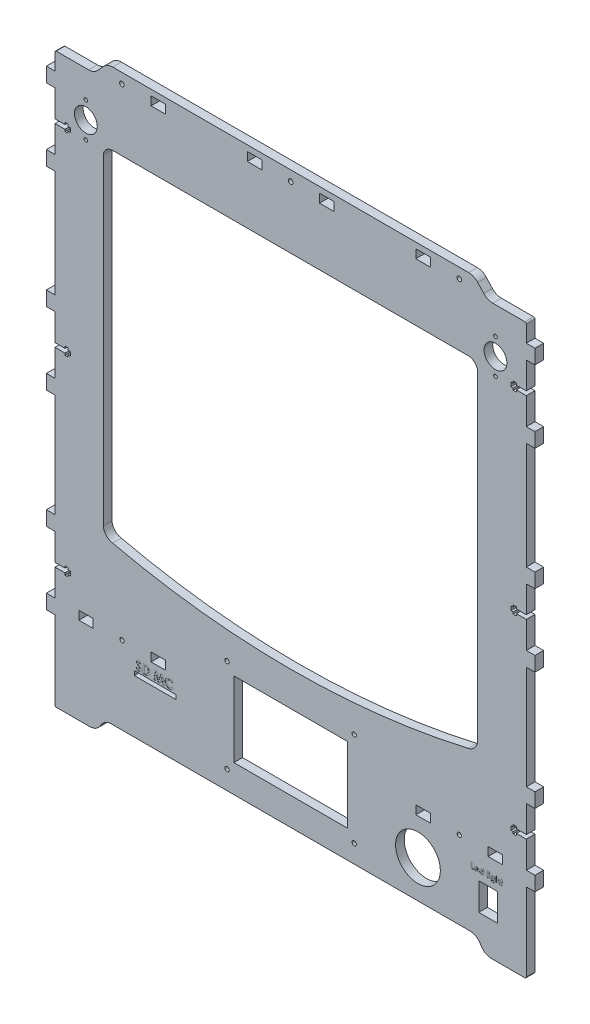
SolidWorks part; units mm, degrees
ref_plane "Спереди" through (0, 0, 0) normal (0, 0, 1) x (1, 0, 0)
ref_plane "Сверху" through (0, 0, 0) normal (0, 1, 0) x (1, 0, 0)
ref_plane "Справа" through (0, 0, 0) normal (1, 0, 0) x (0, 0, -1)
sketch "Эскиз1" plane through (0, 0, 0) normal (0, 0, 1) x (1, 0, 0)
  line L0 (-95.8892, 197.3491) -> (-85.8892, 197.3491)
  line L1 (-85.8892, 197.3491) -> (-85.8892, 191.3491)
  line L2 (-85.8892, 191.3491) -> (-95.8892, 191.3491)
  line L3 (-95.8892, 191.3491) -> (-95.8892, 197.3491)
  line L4 (97.3908, 191.3491) -> (87.3908, 191.3491)
  line L5 (87.3908, 191.3491) -> (87.3908, 197.3491)
  line L6 (87.3908, 197.3491) -> (97.3908, 197.3491)
  line L7 (97.3908, 197.3491) -> (97.3908, 191.3491)
  line L8 (97.3654, -141.9477) -> (87.3654, -141.9477)
  line L9 (87.3654, -141.9477) -> (87.3654, -135.9477)
  line L10 (87.3654, -135.9477) -> (97.3654, -135.9477)
  line L11 (97.3654, -135.9477) -> (97.3654, -141.9477)
  line L12 (147.3854, -141.9477) -> (137.3854, -141.9477)
  line L13 (137.3854, -141.9477) -> (137.3854, -135.9477)
  line L14 (137.3854, -135.9477) -> (147.3854, -135.9477)
  line L15 (147.3854, -135.9477) -> (147.3854, -141.9477)
  line L16 (-135.8946, -141.9477) -> (-145.8946, -141.9477)
  line L17 (-145.8946, -141.9477) -> (-145.8946, -135.9477)
  line L18 (-145.8946, -135.9477) -> (-135.8946, -135.9477)
  line L19 (-135.8946, -135.9477) -> (-135.8946, -141.9477)
  line L20 (-85.8746, -141.9477) -> (-95.8746, -141.9477)
  line L21 (-95.8746, -141.9477) -> (-95.8746, -135.9477)
  line L22 (-95.8746, -135.9477) -> (-85.8746, -135.9477)
  line L23 (-85.8746, -135.9477) -> (-85.8746, -141.9477)
  line L24 (-19.2392, 191.3491) -> (-29.2392, 191.3491)
  line L25 (-29.2392, 191.3491) -> (-29.2392, 197.3491)
  line L26 (-29.2392, 197.3491) -> (-19.2392, 197.3491)
  line L27 (-19.2392, 197.3491) -> (-19.2392, 191.3491)
  line L28 (30.7408, 191.3491) -> (20.7408, 191.3491)
  line L29 (20.7408, 191.3491) -> (20.7408, 197.3491)
  line L30 (20.7408, 197.3491) -> (30.7408, 197.3491)
  line L31 (30.7408, 197.3491) -> (30.7408, 191.3491)
  line L32 (-122.3991, 151.3491) -> (123.6241, 151.3491)
  line L33 (40.0454, -173.6357) -> (40.0454, -121.6361)
  line L34 (40.0454, -121.6361) -> (-38.5546, -121.6361)
  line L35 (-38.5546, -121.6361) -> (-38.5546, -173.6357)
  line L36 (-38.5546, -173.6357) -> (40.0454, -173.6357)
  line L37 (143.9388, -159.6762) -> (143.9388, -178.6762)
  line L38 (143.9388, -178.6762) -> (130.9388, -178.6762)
  line L39 (130.9388, -178.6762) -> (130.9388, -159.6762)
  line L40 (130.9388, -159.6762) -> (143.9388, -159.6762)
  line L41 (-162.3492, -146.9309) -> (-168.3546, -146.9309)
  line L42 (-168.3546, -146.9309) -> (-168.3546, -136.9309)
  line L43 (-168.3546, -136.9309) -> (-162.3546, -136.9309)
  line L44 (-162.3546, -136.9309) -> (-162.3546, -118.3209)
  line L45 (-162.3546, -96.9409) -> (-168.3546, -96.9409)
  line L46 (-168.3546, -96.9409) -> (-168.3546, -86.9409)
  line L47 (-168.3546, -86.9409) -> (-162.3546, -86.9409)
  line L48 (-162.3546, -86.9409) -> (-162.3546, -15.2109)
  line L49 (-162.3546, -15.2109) -> (-168.3546, -15.2109)
  line L50 (-162.3546, 34.7891) -> (-168.3546, 34.7891)
  line L51 (-168.3546, -5.2109) -> (-162.3546, -5.2109)
  line L52 (-168.3546, 44.7891) -> (-162.3546, 44.7891)
  line L56 (-162.3546, 128.9491) -> (-162.3546, 147.5491)
  line L57 (-162.3492, 168.9491) -> (-168.3492, 168.9491)
  line L58 (-168.3492, 168.9491) -> (-168.3492, 178.9491)
  line L59 (-168.3492, 178.9491) -> (-162.3492, 178.9491)
  line L60 (-162.3492, 178.9491) -> (-162.3492, 190.3491)
  line L61 (-162.3492, -200.9709) -> (-162.3492, -146.9309)
  line L62 (163.8454, -146.9309) -> (169.8454, -146.9309)
  line L63 (169.8454, -146.9309) -> (169.8454, -136.9309)
  line L64 (169.8454, -136.9309) -> (163.8513, -136.9309)
  line L65 (163.8513, -136.9309) -> (163.8513, -118.3209)
  line L66 (163.9392, -96.9409) -> (169.8512, -96.9409)
  line L67 (169.8512, -96.9409) -> (169.8512, -86.9409)
  line L68 (169.8512, -86.9409) -> (163.8512, -86.9409)
  line L69 (163.8512, -86.9409) -> (163.8512, -15.2109)
  line L70 (163.8512, -15.2109) -> (169.8512, -15.2109)
  line L71 (163.8512, 34.7891) -> (169.8512, 34.7891)
  line L72 (169.8512, -5.2109) -> (163.8512, -5.2109)
  line L73 (169.8512, 44.7891) -> (163.8512, 44.7891)
  line L74 (163.8512, 118.9491) -> (169.8512, 118.9491)
  line L75 (169.8512, 118.9491) -> (169.8512, 128.9491)
  line L76 (169.8512, 128.9491) -> (163.8512, 128.9491)
  line L77 (163.8512, 128.9491) -> (163.8512, 147.5491)
  line L78 (163.8508, 168.9491) -> (169.8508, 168.9491)
  line L79 (169.8508, 168.9491) -> (169.8508, 178.9491)
  line L80 (169.8508, 178.9491) -> (163.8508, 178.9491)
  line L81 (163.8508, 178.9491) -> (163.8508, 190.3491)
  line L82 (156.9388, 150.3491) -> (156.9388, 151.7492)
  line L83 (163.9392, -115.5209) -> (156.9392, -115.5209)
  line L84 (156.9392, -114.1224) -> (154.7382, -114.1224)
  line L85 (156.9399, -118.3209) -> (163.8513, -118.3209)
  line L86 (153.2384, -118.3222) -> (154.7405, -118.3222)
  line L87 (-155.4441, 11.989) -> (-153.2432, 11.989)
  line L88 (154.7382, -114.1224) -> (154.7382, -115.5222)
  line L89 (154.7391, 16.1893) -> (153.24, 16.1893)
  line L90 (153.2384, -115.5222) -> (153.2384, -118.3222)
  line L91 (-155.4426, -119.721) -> (-153.2418, -119.721)
  line L92 (163.8508, 150.3491) -> (156.9388, 150.3491)
  line L93 (156.9399, -119.7231) -> (156.9399, -118.3209)
  line L94 (156.9392, -115.5209) -> (156.9392, -114.1224)
  line L95 (154.7382, -115.5222) -> (153.2384, -115.5222)
  line L96 (154.741, 147.5502) -> (154.741, 146.1493)
  line L97 (-155.4451, -114.1209) -> (-155.4451, -115.5209)
  line L98 (154.7415, 13.3902) -> (154.7415, 11.9893)
  line L99 (-162.3546, 147.5491) -> (-155.4441, 147.5491)
  line L100 (-155.4441, 147.5491) -> (-155.4441, 146.149)
  line L101 (-155.4398, 150.3491) -> (-162.3492, 150.3491)
  line L102 (-153.2398, 150.3482) -> (-153.2398, 151.7491)
  line L103 (154.7405, -118.3222) -> (154.7405, -119.7231)
  line L104 (-155.4451, -115.5209) -> (-162.3546, -115.5209)
  line L105 (154.741, 151.7492) -> (154.741, 150.3493)
  line L106 (156.9417, 146.1493) -> (156.9417, 147.5491)
  line L107 (-153.2432, 13.3622) -> (-151.7428, 13.3622)
  line L108 (-155.4426, -118.3209) -> (-155.4426, -119.721)
  line L109 (153.241, 150.3493) -> (153.241, 147.5502)
  line L110 (-153.2451, 17.5891) -> (-155.4451, 17.5891)
  line L111 (-162.3546, 13.3891) -> (-155.4441, 13.3891)
  line L112 (154.741, 146.1493) -> (156.9417, 146.1493)
  line L113 (153.241, 147.5502) -> (154.741, 147.5502)
  line L114 (-153.2433, 147.5489) -> (-151.7375, 147.5489)
  line L115 (-151.7428, 13.3622) -> (-151.7428, 16.1885)
  line L116 (163.8512, 16.1891) -> (156.9392, 16.1891)
  line L117 (154.7391, 17.5621) -> (154.7391, 16.1893)
  line L118 (154.741, 150.3493) -> (153.241, 150.3493)
  line L119 (154.7415, 11.9893) -> (156.9417, 11.9893)
  line L120 (-153.2451, -114.1209) -> (-155.4451, -114.1209)
  line L121 (-151.7436, -118.3211) -> (-151.7436, -115.5218)
  line L122 (-153.2418, -118.3211) -> (-151.7436, -118.3211)
  line L123 (-153.2432, 11.989) -> (-153.2432, 13.3622)
  line L124 (156.9417, 13.3891) -> (163.8512, 13.3891)
  line L125 (-162.3546, -118.3209) -> (-155.4426, -118.3209)
  line L126 (153.24, 16.1893) -> (153.24, 13.3902)
  line L127 (-153.2451, -115.5218) -> (-153.2451, -114.1209)
  line L128 (-151.7428, 16.1885) -> (-153.2451, 16.1885)
  line L129 (-155.4441, 146.149) -> (-153.2433, 146.149)
  line L130 (-153.2418, -119.721) -> (-153.2418, -118.3211)
  line L131 (-155.4398, 151.7491) -> (-155.4398, 150.3491)
  line L132 (-151.7436, -115.5218) -> (-153.2451, -115.5218)
  line L133 (-153.2433, 146.149) -> (-153.2433, 147.5489)
  line L134 (153.24, 13.3902) -> (154.7415, 13.3902)
  line L135 (156.9388, 151.7492) -> (154.741, 151.7492)
  line L136 (-151.7375, 147.5489) -> (-151.738, 150.3482)
  line L137 (156.9417, 147.5491) -> (163.8512, 147.5491)
  line L138 (-155.4451, 16.1891) -> (-162.3546, 16.1891)
  line L139 (156.9417, 11.9893) -> (156.9417, 13.3891)
  line L140 (-155.4451, 17.5891) -> (-155.4451, 16.1891)
  line L141 (154.7405, -119.7231) -> (156.9399, -119.7231)
  line L142 (-153.2398, 151.7491) -> (-155.4398, 151.7491)
  line L143 (156.9392, 17.5621) -> (154.7391, 17.5621)
  line L144 (-151.738, 150.3482) -> (-153.2398, 150.3482)
  line L145 (-162.3546, -115.5209) -> (-162.3546, -96.9409)
  line L146 (-162.3492, 150.3491) -> (-162.3492, 168.9491)
  line L147 (163.9392, -115.5209) -> (163.9392, -96.9409)
  line L148 (163.8508, 150.3491) -> (163.8508, 168.9491)
  line L149 (-139.0924, 191.3491) -> (-161.5253, 191.3491)
  line L150 (-128.7242, 198.5879) -> (-132.8221, 194.1104)
  line L151 (123.9554, 201.3491) -> (-122.4539, 201.3491)
  line L152 (130.2257, 198.5879) -> (134.3236, 194.1104)
  line L153 (140.5939, 191.3491) -> (162.8508, 191.3491)
  line L154 (-131.8015, -198.9146) -> (-129.7448, -195.8949)
  line L155 (162.7628, -201.9477) -> (139.7264, -201.9477)
  line L156 (133.303, -198.9146) -> (131.2463, -195.8949)
  line L157 (-161.4373, -201.9509) -> (-138.3129, -201.9509)
  line L158 (-123.2334, -192.8586) -> (124.7349, -192.8586)
  line L159 (163.8454, -200.9731) -> (163.8454, -146.9309)
  line L160 (-162.3546, 13.3891) -> (-162.3546, -5.2109)
  line L161 (-168.3546, -15.2109) -> (-168.3546, -5.2109)
  line L162 (-168.3546, 34.7891) -> (-168.3546, 44.7891)
  line L163 (-162.3546, 44.7891) -> (-162.3546, 118.9491)
  line L164 (163.8512, 13.3891) -> (163.8512, -5.2109)
  line L165 (169.8512, -15.2109) -> (169.8512, -5.2109)
  line L166 (169.8512, 34.7891) -> (169.8512, 44.7891)
  line L167 (163.8512, 44.7891) -> (163.8512, 118.9491)
  line L168 (-155.4441, 13.3891) -> (-155.4441, 11.989)
  line L169 (-153.2451, 16.1885) -> (-153.2451, 17.5891)
  line L170 (156.9392, 16.1891) -> (156.9392, 17.5621)
  line L171 (-162.3546, 34.7891) -> (-162.3546, 16.1891)
  line L172 (163.8512, 34.7891) -> (163.8512, 16.1891)
  line L173 (-107.5042, -155.9271) -> (-107.5042, -152.9271)
  line L174 (-107.5042, -152.9271) -> (-78.5042, -152.9271)
  line L175 (-78.5042, -152.9271) -> (-78.5042, -155.9271)
  line L176 (-78.5042, -155.9271) -> (-107.5042, -155.9271)
  line L177 (-162.3546, 128.9491) -> (-168.3546, 128.9491)
  line L178 (-162.3546, 118.9491) -> (-168.3546, 118.9491)
  line L179 (-168.3546, 118.9491) -> (-168.3546, 128.9491)
  line L180 (-155.4426, -141.9477) -> (156.9399, -141.9477) construction
  line L181 (-140.9992, 144.3414) -> (-140.9992, 175.9536) construction
  line L182 (142.5008, 178.9491) -> (142.5008, 143.1493) construction
  line L183 (130.1588, 145.3729) -> (130.1254, -76.9742)
  line L184 (-128.9341, 145.3729) -> (-128.9472, -76.974)
  arc A0 (-122.4711, -84.0153) -> (123.6489, -84.0153) centre (0.5889, 449.8336) ccw
  circle A3 centre (44.7454, -115.1361) radius 1.5
  circle A4 centre (44.7454, -180.3857) radius 1.5
  circle A5 centre (-43.2546, -179.8825) radius 1.5
  circle A6 centre (-43.2546, -115.1361) radius 1.5
  circle A7 centre (88.8454, -166.9477) radius 15.5
  arc A8 (130.1588, 145.3729) -> (123.6241, 151.3491) centre (123.6241, 144.7884) ccw
  arc A9 (-122.3991, 151.3491) -> (-128.9341, 145.3729) centre (-122.472, 144.8677) ccw
  arc A10 (-128.9472, -76.974) -> (-122.4711, -84.0153) centre (-121.245, -76.3888) ccw
  arc A11 (123.6489, -84.0153) -> (130.1254, -76.9742) centre (121.7477, -75.7674) ccw
  circle A12 centre (0.7508, 194.3491) radius 1.6
  circle A13 centre (-116.0492, 194.3491) radius 1.6
  arc A14 (134.3236, 194.1104) -> (140.5939, 191.3491) centre (140.5939, 199.8491) ccw
  arc A15 (-161.5253, 191.3491) -> (-162.3492, 190.3491) centre (-161.4373, 190.4372) ccw
  arc A16 (-139.0924, 191.3491) -> (-132.8221, 194.1104) centre (-139.0924, 199.8491) ccw
  arc A17 (-122.4539, 201.3491) -> (-128.7242, 198.5879) centre (-122.4539, 192.8491) ccw
  circle A18 centre (117.5508, 194.3491) radius 1.6
  arc A19 (130.2257, 198.5879) -> (123.9554, 201.3491) centre (123.9554, 192.8491) ccw
  arc A20 (163.8508, 190.3491) -> (162.8508, 191.3491) centre (162.8508, 190.3491) ccw
  arc A21 (-123.2334, -192.8586) -> (-129.7448, -195.8949) centre (-123.2334, -201.3586) ccw
  arc A22 (-138.3129, -201.9509) -> (-131.8015, -198.9146) centre (-138.3129, -193.4509) ccw
  arc A23 (131.2463, -195.8949) -> (124.7349, -192.8586) centre (124.7349, -201.3586) ccw
  arc A24 (133.303, -198.9146) -> (139.7264, -201.9477) centre (139.7677, -193.542) ccw
  arc A25 (-162.3492, -200.9709) -> (-161.4373, -201.9509) centre (-161.3926, -200.9949) ccw
  arc A26 (162.7628, -201.9477) -> (163.8454, -200.9731) centre (162.8028, -200.9035) ccw
  circle A27 centre (-140.9992, 160.3491) radius 7.9
  circle A28 centre (142.5008, 160.3491) radius 7.9
  circle A29 centre (-115.9946, -138.9477) radius 1.5
  circle A30 centre (117.4854, -138.9477) radius 1.5
  circle A31 centre (-140.9992, 172.3491) radius 1.25
  circle A32 centre (-140.9992, 148.3491) radius 1.25
  circle A33 centre (142.5008, 172.3491) radius 1.25
  circle A34 centre (142.5008, 148.3491) radius 1.25
  point P239 (87.3908, 194.3491)
  point P241 (-162.3492, 184.6491)
  dimension "D11" = 15.8
  dimension "D12" = 15.8
  dimension "D53" = 31
  dimension "D88" = 283.5
  dimension "D115" = 2.5
  dimension "D113" = 2.5
  dimension "D116" = 12
  dimension "D117" = 12
  dimension "D118" = 2.5
  dimension "D119" = 2.5
  dimension "D120" = 12
  dimension "D121" = 12
  dimension "D1" = 10
  dimension "D2" = 12.4
  dimension "D3" = 12.4
  dimension "D4" = 10
  dimension "D5" = 18.6
  dimension "D6" = 2.8
  dimension "D7" = 18.6
  dimension "D8" = 10
  dimension "D9" = 10
  dimension "D10" = 10
  dimension "D13" = 6
  dimension "D14" = 18.6
  dimension "D15" = 18.6
  dimension "D16" = 10
  dimension "D17" = 74.16
  dimension "D18" = 74.16
  dimension "D19" = 10
  dimension "D20" = 10
  dimension "D21" = 18.6
  dimension "D22" = 18.6
  dimension "D23" = 18.6
  dimension "D24" = 18.6
  dimension "D25" = 10
  dimension "D26" = 10
  dimension "D27" = 71.73
  dimension "D28" = 71.73
  dimension "D29" = 10
  dimension "D30" = 10
  dimension "D31" = 18.58
  dimension "D32" = 18.58
  dimension "D33" = 18.61
  dimension "D34" = 18.61
  dimension "D35" = 10
  dimension "D36" = 10
  dimension "D37" = 54.04
  dimension "D38" = 54.0422
  dimension "D39" = 403.2968
  dimension "D40" = 2.8
  dimension "D41" = 2.8
  dimension "D42" = 2.8
  dimension "D43" = 2.8
  dimension "D44" = 403.3
  dimension "D45" = 10
  dimension "D46" = 10
  dimension "D47" = 10
  dimension "D48" = 169.1
  dimension "D49" = 10
  dimension "D50" = 10
  dimension "D51" = 10
  dimension "D52" = 10
  dimension "D54" = 338.2
  dimension "D55" = 169.1
  dimension "D56" = 10
  dimension "D57" = 52.3
  dimension "D58" = 52.3
  dimension "D59" = 72.46
  dimension "D60" = 72.46
  dimension "D61" = 56.65
  dimension "D62" = 56.65
  dimension "D63" = 19.99
  dimension "D64" = 19.99
  dimension "D65" = 21.35
  dimension "D66" = 21.35
  dimension "D67" = 22.46
  dimension "D68" = 22.46
  dimension "D69" = 19.9
  dimension "D70" = 19.9
  dimension "D71" = 20.12
  dimension "D72" = 20.12
  dimension "D73" = 47.32
  dimension "D74" = 78.6
  dimension "D75" = 47.32
  dimension "D76" = 4.7
  dimension "D77" = 4.7
  dimension "D78" = 4.7
  dimension "D79" = 4.7
  dimension "D80" = 6.5
  dimension "D81" = 6.5
  dimension "D82" = 6
  dimension "D83" = 60
  dimension "D84" = 55.02
  dimension "D85" = 6
  dimension "D86" = 29
  dimension "D87" = 3
  dimension "D89" = 4
  dimension "D90" = 7
  dimension "D91" = 6
  dimension "D92" = 4
  dimension "D93" = 6
  dimension "D94" = 7
  dimension "D95" = 4
  dimension "D96" = 6
  dimension "D97" = 4
  dimension "D98" = 2.8
  dimension "D99" = 7
  dimension "D100" = 31
  dimension "D101" = 31
  dimension "D102" = 166.56
  dimension "D103" = 131.73
  dimension "D104" = 51.9996
  dimension "D105" = 6
  dimension "D106" = 3
  dimension "D107" = 6
  dimension "D108" = 3
  dimension "D109" = 6
  dimension "D110" = 25
  dimension "D111" = 6
  dimension "D112" = 75
  dimension "D114" = 326.2
  dimension "D122" = 50
  dimension "D123" = 13
  dimension "D124" = 19
extrude "Бобышка-Вытянуть2" add sketch "Эскиз1" along normal blind 6 contours A5 | A4 | A3 | A13 | A12 | A7 | A6 | L32 A8 L183 A11 A0 A10 L184 A9 | A18 | A30 | A29 | A28 | A27 | L4 L5 L6 L7 | L0 L1 L2 L3 | L20 L21 L22 L23 | L16 L17 L18 L19 | L12 L13 L14 L15 | L8 L9 L10 L11 | L37 L38 L39 L40 | L33 L34 L35 L36 | L28 L29 L30 L31 | L24 L25 L26 L27 | L41 L42 L43 L44 L125 L108 L91 L130 L122 L121 L132 L127 L120 L97 L104 L145 L45 L46 L47 L48 L49 L161 L51 L160 L111 L168 L87 L123 L107 L115 L128 L169 L110 L140 L138 L171 L50 L162 L52 L163 L178 L179 L177 L56 L99 L100 L129 L133 L114 L136 L144 L102 L142 L131 L101 L146 L57 L58 L59 L60 A15 L149 A16 L150 A17 L151 A19 L152 A14 L153 A20 L81 L80 L79 L78 L148 L92 L82 L135 L105 L118 L109 L113 L96 L112 L106 L137 L77 L76 L75 L74 L167 L73 L166 L71 L172 L116 L170 L143 L117 L89 L126 L134 L98 L119 L139 L124 L164 L72 L165 L70 L69 L68 L67 L66 L147 L83 L94 L84 L88 L95 L90 L86 L103 L141 L93 L85 L65 L64 L63 L62 L159 A26 L155 A24 L156 A23 L158 A21 L154 A22 L157 A25 L61 | L173 L174 L175 L176 | A32 | A31 | A33 | A34
sketch "Эскиз3" plane through (0, 0, 6) normal (0, 0, 1) x (1, 0, 0)
  line L0 (-107.2394, -151.5718) -> (-78.6482, -151.5718) construction
  text T0 "<b>SD MC</b>" font "Century Gothic" height 6
extrude "Вырез-Вытянуть2" cut sketch "Эскиз3" against normal blind 0.1
sketch "Эскиз4" plane through (0, 0, 6) normal (0, 0, 1) x (1, 0, 0)
  line L0 (124.0715, -154.8104) -> (149.0052, -154.8104) construction
  text T0 "<b>Led light</b>" font "Century Gothic" height 4
extrude "Вырез-Вытянуть3" cut sketch "Эскиз4" against normal blind 0.1
